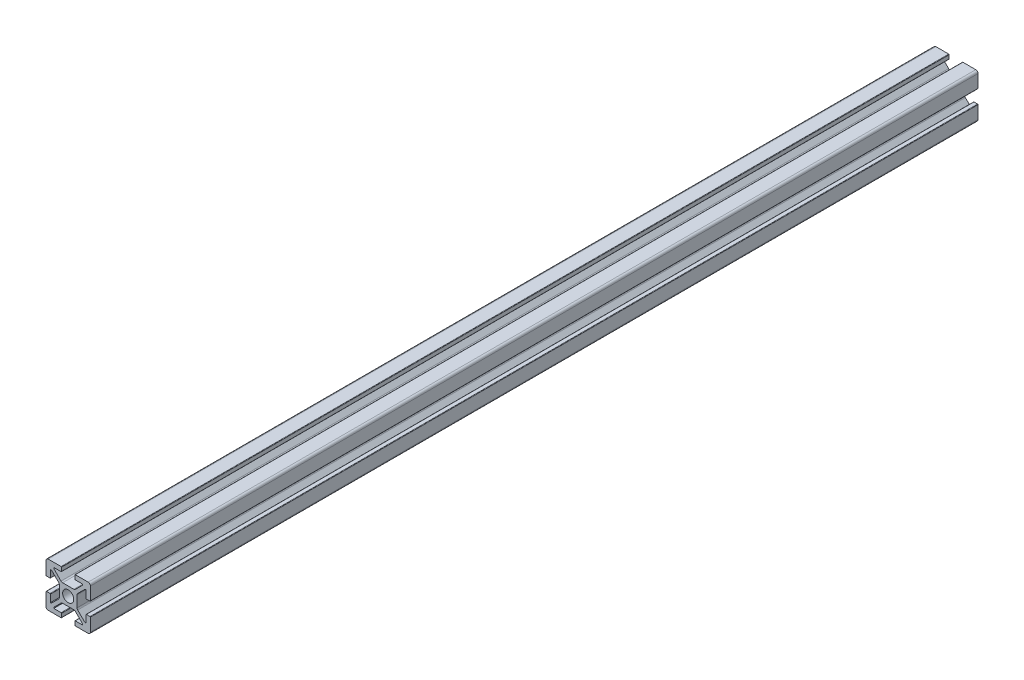
SolidWorks part; units mm, degrees
ref_plane "Front Plane" through (0, 0, 0) normal (0, 0, 1) x (1, 0, 0)
ref_plane "Top Plane" through (0, 0, 0) normal (0, 1, 0) x (1, 0, 0)
ref_plane "Right Plane" through (0, 0, 0) normal (1, 0, 0) x (0, 0, -1)
sketch "Sketch1" plane through (0, 0, 0) normal (0, 0, 1) x (1, 0, 0)
  line L0 (0.2, 13) -> (1.8, 13)
  line L1 (13.2, 0) -> (19, 0)
  line L2 (0, 13.2) -> (0, 19)
  line L3 (1, 20) -> (6.8, 20)
  line L4 (20, 1) -> (20, 6.8)
  line L5 (2, 13.2) -> (2, 16.5)
  line L6 (2, 16.5) -> (2.4393, 16.5)
  line L7 (2.4393, 16.5) -> (5.7071, 13.2322)
  line L8 (6, 12.5251) -> (6, 7.4749)
  line L11 (7.4749, 14) -> (10, 14)
  line L12 (3.5, 17.5607) -> (6.7678, 14.2929)
  line L13 (3.5, 18) -> (3.5, 17.5607)
  line L14 (6.8, 18) -> (3.5, 18)
  line L15 (6.8, 20) -> (1, 20)
  line L16 (7, 19.8) -> (7, 18.2)
  line L17 (19.8, 7) -> (18.2, 7)
  line L18 (20, 6.8) -> (20, 1)
  line L19 (18, 6.8) -> (18, 3.5)
  line L20 (18, 3.5) -> (17.5607, 3.5)
  line L21 (17.5607, 3.5) -> (14.2929, 6.7678)
  line L22 (14, 7.4749) -> (14, 12.5251)
  line L23 (12.5251, 6) -> (10, 6)
  line L24 (16.5, 2.4393) -> (13.2322, 5.7071)
  line L25 (16.5, 2) -> (16.5, 2.4393)
  line L26 (13.2, 2) -> (16.5, 2)
  line L27 (13.2, 0) -> (19, 0)
  line L28 (13, 0.2) -> (13, 1.8)
  line L30 (13, 19.8) -> (13, 18.2)
  line L31 (13.2, 20) -> (19, 20)
  line L32 (13.2, 18) -> (16.5, 18)
  line L33 (16.5, 18) -> (16.5, 17.5607)
  line L34 (16.5, 17.5607) -> (13.2322, 14.2929)
  line L35 (12.5251, 14) -> (10, 14)
  line L36 (17.5607, 16.5) -> (14.2929, 13.2322)
  line L37 (18, 16.5) -> (17.5607, 16.5)
  line L38 (18, 13.2) -> (18, 16.5)
  line L39 (20, 13.2) -> (20, 19)
  line L40 (19.8, 13) -> (18.2, 13)
  line L41 (7, 0.2) -> (7, 1.8)
  line L42 (6.8, 0) -> (1, 0)
  line L43 (6.8, 2) -> (3.5, 2)
  line L44 (3.5, 2) -> (3.5, 2.4393)
  line L45 (3.5, 2.4393) -> (6.7678, 5.7071)
  line L46 (7.4749, 6) -> (10, 6)
  line L47 (2.4393, 3.5) -> (5.7071, 6.7678)
  line L48 (2, 3.5) -> (2.4393, 3.5)
  line L49 (2, 6.8) -> (2, 3.5)
  line L50 (20, 19) -> (20, 13.2)
  line L51 (1, 0) -> (6.8, 0)
  line L52 (0, 6.8) -> (0, 1)
  line L53 (13.2, 20) -> (19, 20)
  line L54 (0.2, 7) -> (1.8, 7)
  arc A0 (20, 1) -> (19, 0) centre (19, 1) cw
  arc A1 (1, 0) -> (0, 1) centre (1, 1) cw
  arc A2 (0, 19) -> (1, 20) centre (1, 19) cw
  arc A3 (20, 19) -> (19, 20) centre (19, 19) ccw
  arc A4 (14.2929, 6.7678) -> (14, 7.4749) centre (15, 7.4749) cw
  arc A5 (12.5251, 6) -> (13.2322, 5.7071) centre (12.5251, 5) cw
  arc A6 (6.7678, 5.7071) -> (7.4749, 6) centre (7.4749, 5) cw
  arc A7 (5.7071, 6.7678) -> (6, 7.4749) centre (5, 7.4749) ccw
  arc A8 (14.2929, 13.2322) -> (14, 12.5251) centre (15, 12.5251) ccw
  arc A9 (13.2322, 14.2929) -> (12.5251, 14) centre (12.5251, 15) cw
  arc A10 (6, 12.5251) -> (5.7071, 13.2322) centre (5, 12.5251) ccw
  arc A11 (7.4749, 14) -> (6.7678, 14.2929) centre (7.4749, 15) cw
  arc A12 (0, 6.8) -> (0.2, 7) centre (0.2, 6.8) cw
  arc A13 (2, 6.8) -> (1.8, 7) centre (1.8, 6.8) ccw
  arc A14 (7, 1.8) -> (6.8, 2) centre (6.8, 1.8) ccw
  arc A15 (7, 0.2) -> (6.8, 0) centre (6.8, 0.2) cw
  arc A16 (13.2, 0) -> (13, 0.2) centre (13.2, 0.2) cw
  arc A17 (13.2, 2) -> (13, 1.8) centre (13.2, 1.8) ccw
  arc A18 (18.2, 7) -> (18, 6.8) centre (18.2, 6.8) ccw
  arc A19 (19.8, 7) -> (20, 6.8) centre (19.8, 6.8) cw
  arc A20 (20, 13.2) -> (19.8, 13) centre (19.8, 13.2) cw
  arc A21 (18, 13.2) -> (18.2, 13) centre (18.2, 13.2) ccw
  arc A22 (13, 19.8) -> (13.2, 20) centre (13.2, 19.8) cw
  arc A23 (13, 18.2) -> (13.2, 18) centre (13.2, 18.2) ccw
  arc A24 (6.8, 18) -> (7, 18.2) centre (6.8, 18.2) ccw
  arc A25 (7, 19.8) -> (6.8, 20) centre (6.8, 19.8) ccw
  arc A26 (1.8, 13) -> (2, 13.2) centre (1.8, 13.2) ccw
  arc A27 (0.2, 13) -> (0, 13.2) centre (0.2, 13.2) cw
  circle A28 centre (10, 10) radius 2.5
  point P19 (2, 13)
  dimension "D1" = 1
  dimension "D4" = 1
  dimension "D5" = 0.2
  dimension "D6" = 0.2
  dimension "D7" = 5
  dimension "D2" = 7
  dimension "D3" = 2
  dimension "D9" = 3.5
extrude "Boss-Extrude1" add sketch "Sketch1" along normal blind 400 contours A27 L0 A26 L5 L6 L7 A10 L8 A7 L47 L48 L49 A13 L54 A12 L52 A1 L42 A15 L41 A14 L43 L44 L45 A6 L46 L23 A5 L24 L25 L26 A17 L28 A16 L1 A0 L4 A19 L17 A18 L19 L20 L21 A4 L22 A8 L36 L37 L38 A21 L40
